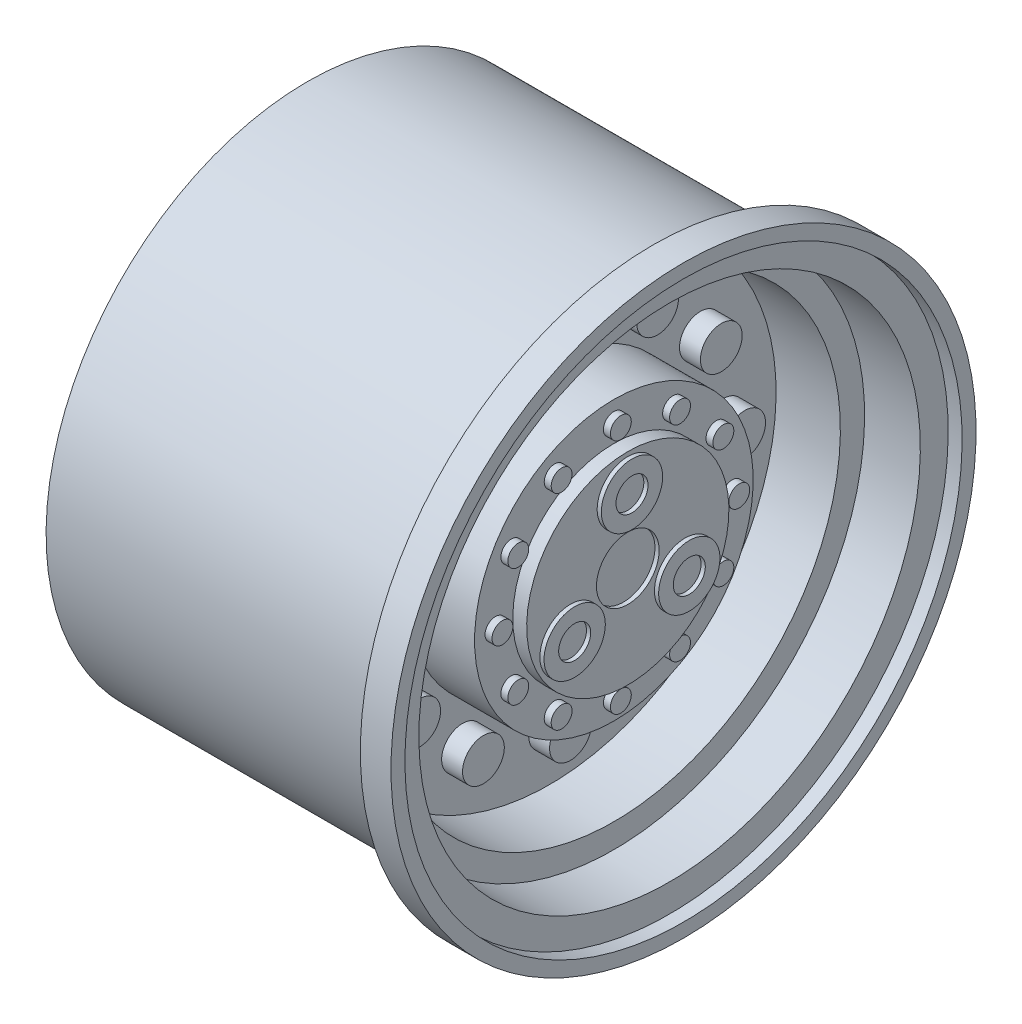
SolidWorks part; units mm, degrees
ref_plane "Front Plane" through (0, 0, 0) normal (0, 0, 1) x (1, 0, 0)
ref_plane "Top Plane" through (0, 0, 0) normal (0, 1, 0) x (1, 0, 0)
ref_plane "Right Plane" through (0, 0, 0) normal (1, 0, 0) x (0, 0, -1)
sketch "Sketch1" plane through (0, 0, 0) normal (0, 0, 1) x (1, 0, 0)
  line L0 (0, 9.38) -> (0, 0) construction
  line L1 (0, 0) -> (3.75, 0) construction
  line L2 (3.75, 0) -> (0, 0)
  line L3 (0, 0) -> (-5.5, 0)
  line L4 (-5.5, 0) -> (-5.5, 3.25)
  line L5 (-5.5, 3.25) -> (-4.75, 3.25)
  line L6 (-4.75, 3.25) -> (-4.75, 4.5)
  line L7 (-4.75, 4.5) -> (-3.85, 4.5)
  line L8 (-3.85, 4.5) -> (-3.85, 8.13)
  line L9 (-3.85, 8.13) -> (-6.25, 8.13)
  line L10 (-6.25, 8.13) -> (-6.25, 8.5)
  line L11 (-6.25, 8.5) -> (-7.75, 8.5)
  line L12 (-7.75, 8.5) -> (-7.75, 9.38)
  line L13 (-7.75, 9.38) -> (0, 9.38)
  line L14 (0, 9.38) -> (4.65, 9.38)
  line L15 (5.75, 10.5) -> (5.75, 10)
  line L16 (5.75, 10) -> (5.25, 10)
  line L17 (5.25, 10) -> (5.25, 9)
  line L18 (5.25, 9) -> (3.25, 9)
  line L19 (3.25, 9) -> (3.25, 8.13)
  line L20 (3.25, 8.13) -> (0.943, 8.13)
  line L21 (0.943, 8.13) -> (0.943, 5)
  line L22 (0.943, 5) -> (3.25, 5)
  line L23 (3.25, 5) -> (3.25, 3.63)
  line L24 (3.25, 3.63) -> (3.75, 3.63)
  line L25 (3.75, 3.63) -> (3.75, 0)
  line L26 (4.65, 9.38) -> (4.65, 10.5)
  line L27 (4.65, 10.5) -> (5.75, 10.5)
  dimension "D1" = 3.25
  dimension "D2" = 4.5
  dimension "D3" = 8.13
  dimension "D4" = 8.5
  dimension "D5" = 9.38
  dimension "D6" = 1.5
  dimension "D7" = 3.9
  dimension "D8" = 3
  dimension "D9" = 2.25
  dimension "D10" = 13.5
  dimension "D11" = 0.5
  dimension "D12" = 10
  dimension "D13" = 1.1
  dimension "D14" = 2.5
  dimension "D15" = 5.75
  dimension "D16" = 0.5
  dimension "D17" = 10.5
  dimension "D18" = 8.13
  dimension "D19" = 9
  dimension "D20" = 5
  dimension "D21" = 3.63
  dimension "D22" = 0.943
revolve "Revolve1" add sketch "Sketch1" angle 360 about L3
sketch "Sketch2" plane through (0.943, 0, 0) normal (1, 0, 0) x (0, 0, -1)
  circle A0 centre (0, 0) radius 6.25 construction
  circle A1 centre (0, 0) radius 3.63 construction
  circle A2 centre (0, 6.25) radius 0.75
  circle A3 centre (0, 0) radius 6.25 construction
  circle A4 centre (3.125, 5.4127) radius 0.75
  circle A5 centre (0, 0) radius 6.25 construction
  circle A6 centre (5.4127, 3.125) radius 0.75
  circle A7 centre (0, 0) radius 6.25 construction
  circle A8 centre (6.25, 0) radius 0.75
  circle A9 centre (0, 0) radius 6.25 construction
  circle A10 centre (5.4127, -3.125) radius 0.75
  circle A11 centre (0, 0) radius 6.25 construction
  circle A12 centre (3.125, -5.4127) radius 0.75
  circle A13 centre (0, 0) radius 6.25 construction
  circle A14 centre (0, -6.25) radius 0.75
  circle A15 centre (0, 0) radius 6.25 construction
  circle A16 centre (-3.125, -5.4127) radius 0.75
  circle A17 centre (0, 0) radius 6.25 construction
  circle A18 centre (-5.4127, -3.125) radius 0.75
  circle A19 centre (0, 0) radius 6.25 construction
  circle A20 centre (-6.25, 0) radius 0.75
  circle A21 centre (0, 0) radius 6.25 construction
  circle A22 centre (-5.4127, 3.125) radius 0.75
  circle A23 centre (0, 0) radius 6.25 construction
  circle A24 centre (-3.125, 5.4127) radius 0.75
  point P42 (0, 0)
  dimension "D1" = 12.5
  dimension "D2" = 1.5
  dimension "D3" = 12
extrude "Boss-Extrude1" add sketch "Sketch2" along normal blind 0.75
sketch "Sketch3" plane through (3.25, 0, 0) normal (1, 0, 0) x (0, 0, -1)
  circle A0 centre (0, 0) radius 4.25 construction
  circle A1 centre (0, 4.25) radius 0.375
  circle A2 centre (0, 0) radius 4.25 construction
  circle A3 centre (2.125, 3.6806) radius 0.375
  circle A4 centre (0, 0) radius 4.25 construction
  circle A5 centre (3.6806, 2.125) radius 0.375
  circle A6 centre (0, 0) radius 4.25 construction
  circle A7 centre (4.25, 0) radius 0.375
  circle A8 centre (0, 0) radius 4.25 construction
  circle A9 centre (3.6806, -2.125) radius 0.375
  circle A10 centre (0, 0) radius 4.25 construction
  circle A11 centre (2.125, -3.6806) radius 0.375
  circle A12 centre (0, 0) radius 4.25 construction
  circle A13 centre (0, -4.25) radius 0.375
  circle A14 centre (0, 0) radius 4.25 construction
  circle A15 centre (-2.125, -3.6806) radius 0.375
  circle A16 centre (0, 0) radius 4.25 construction
  circle A17 centre (-3.6806, -2.125) radius 0.375
  circle A18 centre (0, 0) radius 4.25 construction
  circle A19 centre (-4.25, 0) radius 0.375
  circle A20 centre (0, 0) radius 4.25 construction
  circle A21 centre (-3.6806, 2.125) radius 0.375
  circle A22 centre (0, 0) radius 4.25 construction
  circle A23 centre (-2.125, 3.6806) radius 0.375
  point P40 (0, 0)
  dimension "D1" = 8.5
  dimension "D2" = 0.75
  dimension "D3" = 12
extrude "Boss-Extrude2" add sketch "Sketch3" along normal blind 0.25
sketch "Sketch5" plane through (3.75, 0, 0) normal (1, 0, 0) x (0, 0, -1)
  circle A0 centre (0, 0) radius 1.125
  dimension "D1" = 2.25
extrude "Cut-Extrude1" cut sketch "Sketch5" against normal blind 0.15
sketch "Sketch6" plane through (3.75, 0, 0) normal (1, 0, 0) x (0, 0, -1)
  circle A0 centre (0, 0) radius 2.375 construction
  circle A1 centre (0, 2.375) radius 1.1
  circle A2 centre (0, 2.375) radius 0.575
  circle A3 centre (0, 0) radius 2.375 construction
  circle A4 centre (2.0568, -1.1875) radius 1.1
  circle A5 centre (2.0568, -1.1875) radius 0.575
  circle A6 centre (0, 0) radius 2.375 construction
  circle A7 centre (-2.0568, -1.1875) radius 1.1
  circle A8 centre (-2.0568, -1.1875) radius 0.575
  point P16 (0, 0)
  dimension "D1" = 4.75
  dimension "D2" = 2.2
  dimension "D3" = 1.15
  dimension "D4" = 3
extrude "Boss-Extrude3" add sketch "Sketch6" along normal blind 0.15
sketch "Sketch7" plane through (-4.75, 0, 0) normal (-1, 0, 0) x (0, 0, 1)
  circle A0 centre (0, 0) radius 3.81 construction
  circle A1 centre (0, 3.81) radius 0.375
  circle A2 centre (0, 0) radius 3.81 construction
  circle A3 centre (1.905, 3.2996) radius 0.375
  circle A4 centre (0, 0) radius 3.81 construction
  circle A5 centre (3.2996, 1.905) radius 0.375
  circle A6 centre (0, 0) radius 3.81 construction
  circle A7 centre (3.81, 0) radius 0.375
  circle A8 centre (0, 0) radius 3.81 construction
  circle A9 centre (3.2996, -1.905) radius 0.375
  circle A10 centre (0, 0) radius 3.81 construction
  circle A11 centre (1.905, -3.2996) radius 0.375
  circle A12 centre (0, 0) radius 3.81 construction
  circle A13 centre (0, -3.81) radius 0.375
  circle A14 centre (0, 0) radius 3.81 construction
  circle A15 centre (-1.905, -3.2996) radius 0.375
  circle A16 centre (0, 0) radius 3.81 construction
  circle A17 centre (-3.2996, -1.905) radius 0.375
  circle A18 centre (0, 0) radius 3.81 construction
  circle A19 centre (-3.81, 0) radius 0.375
  circle A20 centre (0, 0) radius 3.81 construction
  circle A21 centre (-3.2996, 1.905) radius 0.375
  circle A22 centre (0, 0) radius 3.81 construction
  circle A23 centre (-1.905, 3.2996) radius 0.375
  point P40 (0, 0)
  dimension "D1" = 7.62
  dimension "D2" = 0.75
  dimension "D3" = 12
extrude "Boss-Extrude4" add sketch "Sketch7" along normal blind 0.25
sketch "Sketch8" plane through (-5.5, 0, 0) normal (-1, 0, 0) x (0, 0, 1)
  circle A0 centre (0, 0) radius 1.25
  dimension "D1" = 2.5
extrude "Cut-Extrude2" cut sketch "Sketch8" against normal blind 5
